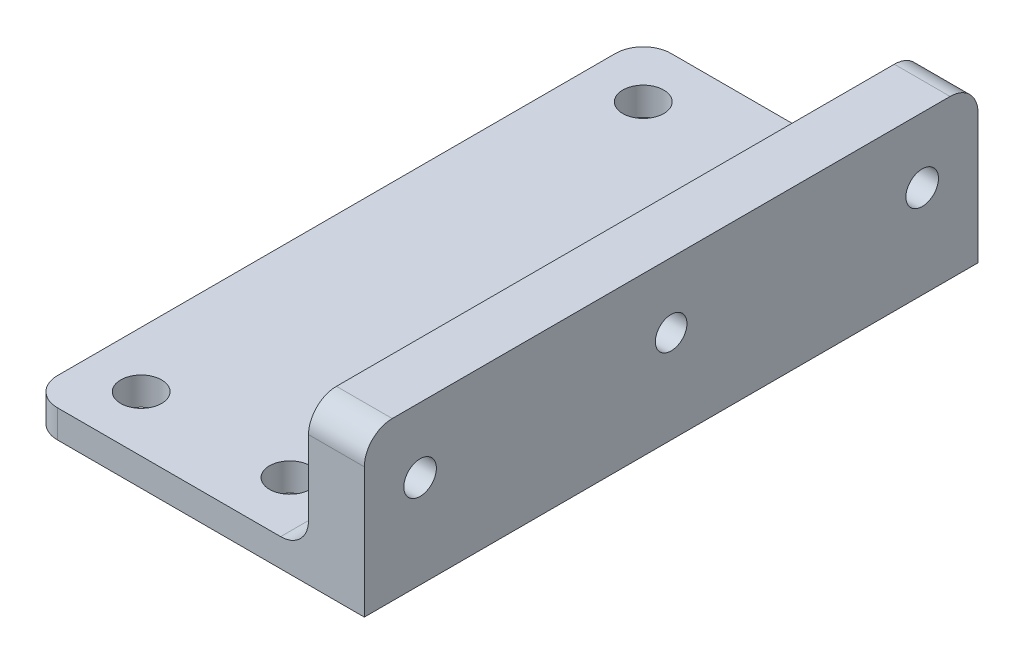
SolidWorks part; units mm, degrees
ref_plane "Front Plane" through (0, 0, 0) normal (0, 0, 1) x (1, 0, 0)
ref_plane "Top Plane" through (0, 0, 0) normal (0, 1, 0) x (1, 0, 0)
ref_plane "Right Plane" through (0, 0, 0) normal (1, 0, 0) x (0, 0, -1)
sketch "Sketch1" plane through (0, 0, 0) normal (0, 1, 0) x (1, 0, 0)
  line L0 (14, 0) -> (14, 66) construction
  line L5 (0, 0) -> (36, 0)
  line L6 (0, 0) -> (0, 66)
  line L7 (0, 66) -> (36, 66)
  line L8 (36, 0) -> (36, 66)
  line L9 (0, 33) -> (36, 33) construction
  circle A4 centre (6, 60) radius 2.2
  circle A5 centre (6, 6) radius 2.2
  circle A6 centre (22, 6) radius 2.2
  circle A7 centre (22, 60) radius 2.2
  dimension "D1" = 66
  dimension "D2" = 22
  dimension "D3" = 4.4
  dimension "D4" = 6
  dimension "D5" = 6
  dimension "D6" = 8
extrude "Boss-Extrude1" add sketch "Sketch1" along normal blind 3
sketch "Sketch2" plane through (0, 3, 0) normal (0, 1, 0) x (1, 0, 0)
  line L0 (36, 66) -> (0, 66) construction
  line L1 (36, 0) -> (30, 0)
  line L2 (36, 0) -> (36, 66)
  line L3 (36, 66) -> (30, 66)
  line L4 (30, 0) -> (30, 66)
  dimension "D1" = 6
extrude "Boss-Extrude2" add sketch "Sketch2" along normal blind 14
sketch "Sketch3" plane through (30, 0, 0) normal (-1, 0, 0) x (0, 0, 1)
  line L0 (-66, 10) -> (0, 10) construction
  line L1 (-66, 17) -> (-66, 3) construction
  line L2 (0, 17) -> (0, 3) construction
  line L3 (-33, 17) -> (-33, 0) construction
  line L4 (-66, 17) -> (0, 17) construction
  line L5 (-66, 0) -> (0, 0) construction
  circle A0 centre (-33, 10) radius 1.7
  circle A1 centre (-6, 10) radius 1.752
  circle A2 centre (-60, 10) radius 1.752
  dimension "D1" = 3.4
  dimension "D2" = 6
extrude "Cut-Extrude1" cut sketch "Sketch3" against normal through all
chamfer "Chamfer1" distance 1.7 angle 45 3 edges at (30, 10, -4.248) (30, 10, -31.3) (30, 10, -61.752)
fillet "Fillet1" radius 3 5 edges at (30, 3, -33) (0, 1.5, 0) (0, 1.5, -66) (33, 17, 0) (33, 17, -66)
